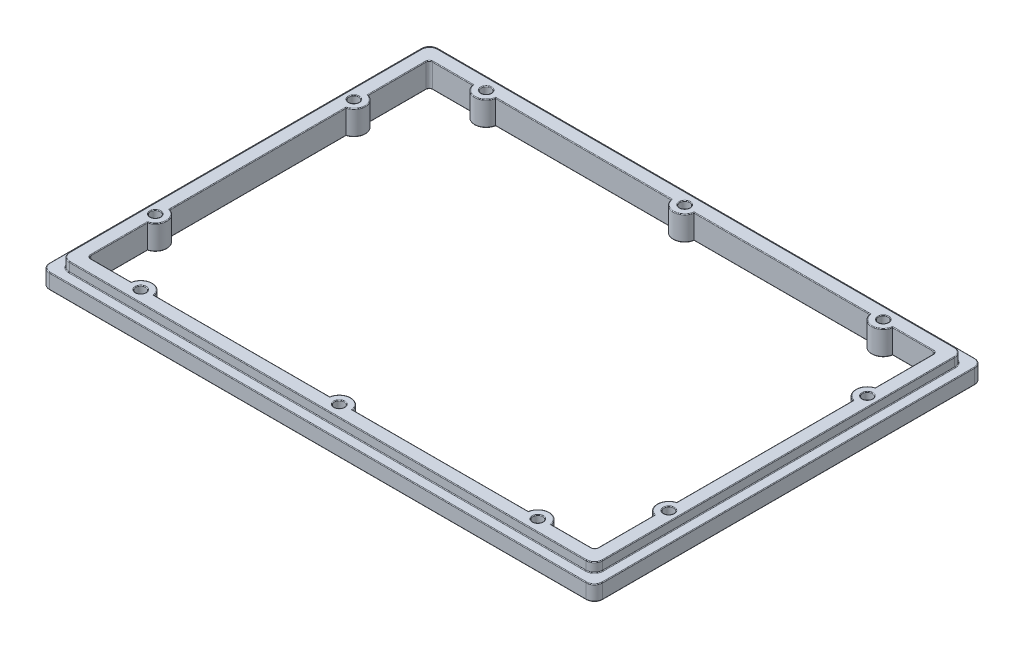
SolidWorks part; units mm, degrees
material "PP Copolymer"
ref_plane "Front Plane" through (0, 0, 0) normal (0, 0, 1) x (1, 0, 0)
ref_plane "Top Plane" through (0, 0, 0) normal (0, 1, 0) x (1, 0, 0)
ref_plane "Right Plane" through (0, 0, 0) normal (1, 0, 0) x (0, 0, -1)
sketch "Sketch1" plane through (0, 0, 0) normal (0, 1, 0) x (1, 0, 0)
  line L1 (-102.997, 74.549) -> (102.997, 74.549)
  line L2 (-106.172, 71.374) -> (-106.172, -71.374)
  line L3 (-102.997, -74.549) -> (102.997, -74.549)
  line L4 (106.172, 71.374) -> (106.172, -71.374)
  arc A0 (-102.997, 74.549) -> (-106.172, 71.374) centre (-102.997, 71.374) ccw
  arc A1 (-106.172, -71.374) -> (-102.997, -74.549) centre (-102.997, -71.374) ccw
  arc A2 (102.997, -74.549) -> (106.172, -71.374) centre (102.997, -71.374) ccw
  arc A3 (106.172, 71.374) -> (102.997, 74.549) centre (102.997, 71.374) ccw
  dimension "D5" = 3.175
  dimension "D1" = 212.344
  dimension "D2" = 106.172
  dimension "D3" = 149.098
  dimension "D4" = 74.549
extrude "Extrude1" add sketch "Sketch1" along normal blind 5.842
sketch "Sketch2" plane through (0, 5.842, 0) normal (0, 1, 0) x (1, 0, 0)
  line L0 (106.172, -71.374) -> (106.172, 71.374) construction
  line L1 (-99.187, 70.739) -> (99.187, 70.739)
  line L2 (-102.362, 67.564) -> (-102.362, -67.564)
  line L3 (-99.187, -70.739) -> (99.187, -70.739)
  line L4 (102.362, 67.564) -> (102.362, -67.564)
  line L5 (102.997, 74.549) -> (-102.997, 74.549) construction
  line L6 (-106.172, 71.374) -> (-106.172, -71.374) construction
  line L7 (-102.997, -74.549) -> (102.997, -74.549) construction
  arc A0 (-99.187, 70.739) -> (-102.362, 67.564) centre (-99.187, 67.564) ccw
  arc A1 (-102.362, -67.564) -> (-99.187, -70.739) centre (-99.187, -67.564) ccw
  arc A2 (99.187, -70.739) -> (102.362, -67.564) centre (99.187, -67.564) ccw
  arc A3 (102.362, 67.564) -> (99.187, 70.739) centre (99.187, 67.564) ccw
  dimension "D5" = 3.175
  dimension "D1" = 3.81
  dimension "D2" = 3.81
  dimension "D3" = 3.81
  dimension "D4" = 3.81
extrude "Extrude2" add sketch "Sketch2" along normal offset from surface (3.556 mm away) 9.398 up to face at (0, 0, 0)
sketch "Sketch3" plane through (0, 9.398, 0) normal (0, 1, 0) x (1, 0, 0)
  line L0 (80.5792, 65.532) -> (96.012, 65.532)
  line L1 (-96.012, 65.532) -> (-80.5792, 65.532)
  line L2 (-97.282, 64.262) -> (-97.282, 42.1057)
  line L3 (-96.012, -65.532) -> (-80.5792, -65.532)
  line L4 (97.282, 64.262) -> (97.282, 42.1057)
  line L5 (97.282, 33.5863) -> (97.282, -34.0943)
  line L6 (4.3792, 65.532) -> (71.8208, 65.532)
  line L7 (-71.8208, 65.532) -> (-4.3792, 65.532)
  line L8 (-97.282, 33.5863) -> (-97.282, -34.0943)
  line L9 (-97.282, -42.6137) -> (-97.282, -64.262)
  line L10 (-71.8208, -65.532) -> (-4.3792, -65.532)
  line L11 (4.3792, -65.532) -> (71.8208, -65.532)
  line L12 (97.282, -42.6137) -> (97.282, -64.262)
  line L13 (80.5792, -65.532) -> (96.012, -65.532)
  arc A0 (-96.012, 65.532) -> (-97.282, 64.262) centre (-96.012, 64.262) ccw
  arc A1 (96.012, 65.532) -> (97.282, 64.262) centre (96.012, 64.262) cw
  arc A2 (97.282, -64.262) -> (96.012, -65.532) centre (96.012, -64.262) cw
  arc A3 (-96.012, -65.532) -> (-97.282, -64.262) centre (-96.012, -64.262) cw
  arc A4 (-4.3792, 65.532) -> (4.3792, 65.532) centre (0, 66.294) ccw
  arc A5 (71.8208, 65.532) -> (80.5792, 65.532) centre (76.2, 66.294) ccw
  arc A6 (-80.5792, 65.532) -> (-71.8208, 65.532) centre (-76.2, 66.294) ccw
  arc A7 (-97.282, 33.5863) -> (-97.282, 42.1057) centre (-98.552, 37.846) ccw
  arc A8 (-97.282, -42.6137) -> (-97.282, -34.0943) centre (-98.552, -38.354) ccw
  arc A9 (4.3792, -65.532) -> (-4.3792, -65.532) centre (0, -66.294) ccw
  arc A10 (80.5792, -65.532) -> (71.8208, -65.532) centre (76.2, -66.294) ccw
  arc A11 (-71.8208, -65.532) -> (-80.5792, -65.532) centre (-76.2, -66.294) ccw
  arc A12 (97.282, 42.1057) -> (97.282, 33.5863) centre (98.552, 37.846) ccw
  arc A13 (97.282, -34.0943) -> (97.282, -42.6137) centre (98.552, -38.354) ccw
  dimension "D5" = 1.27
  dimension "D6" = 8.89
  dimension "D1" = 194.564
  dimension "D2" = 97.282
  dimension "D3" = 131.064
  dimension "D4" = 65.532
  dimension "D7" = 132.588
  dimension "D8" = 66.294
  dimension "D9" = 98.552
  dimension "D10" = 104.14
  dimension "D11" = 27.94
  dimension "D12" = 197.104
  dimension "D13" = 174.752
  dimension "D14" = 22.352
extrude "Extrude3" cut sketch "Sketch3" against normal through all
sketch "Sketch4" plane through (0, 9.398, 0) normal (0, 1, 0) x (1, 0, 0)
  circle A0 centre (-98.552, 37.846) radius 1.905
  circle A1 centre (-76.2, 66.294) radius 1.905
  circle A2 centre (0, 66.294) radius 1.905
  circle A3 centre (76.2, 66.294) radius 1.905
  circle A4 centre (98.552, 37.846) radius 1.905
  circle A5 centre (98.552, -38.354) radius 1.905
  circle A6 centre (76.2, -66.294) radius 1.905
  circle A7 centre (0, -66.294) radius 1.905
  circle A8 centre (-76.2, -66.294) radius 1.905
  circle A9 centre (-98.552, -38.354) radius 1.905
  arc A12 (71.8208, 65.532) -> (80.5792, 65.532) centre (76.2, 66.294) ccw construction
  arc A13 (-4.3792, 65.532) -> (4.3792, 65.532) centre (0, 66.294) ccw construction
  arc A14 (-80.5792, 65.532) -> (-71.8208, 65.532) centre (-76.2, 66.294) ccw construction
  arc A15 (-97.282, 33.5863) -> (-97.282, 42.1057) centre (-98.552, 37.846) ccw construction
  arc A16 (-97.282, -42.6137) -> (-97.282, -34.0943) centre (-98.552, -38.354) ccw construction
  arc A17 (-71.8208, -65.532) -> (-80.5792, -65.532) centre (-76.2, -66.294) ccw construction
  arc A18 (4.3792, -65.532) -> (-4.3792, -65.532) centre (0, -66.294) ccw construction
  arc A19 (80.5792, -65.532) -> (71.8208, -65.532) centre (76.2, -66.294) ccw construction
  arc A20 (97.282, -34.0943) -> (97.282, -42.6137) centre (98.552, -38.354) ccw construction
  arc A21 (97.282, 42.1057) -> (97.282, 33.5863) centre (98.552, 37.846) ccw construction
  dimension "D1" = 3.81
extrude "Extrude4" cut sketch "Sketch4" against normal through all
fillet "Fillet1" radius 0.254 108 edges at (-106.172, 0, 0) (-105.2421, 0, 73.6191) (0, 0, 74.549) (105.2421, 0, 73.6191) (106.172, 0, 0) (105.2421, 0, -73.6191) (-105.2421, 0, -73.6191) (-76.2, 0, -61.849) (-38.1, 0, -65.532) (0, 0, -61.849) (38.1, 0, -65.532) (76.2, 0, -61.849) (88.2956, 0, -65.532) (96.91, 0, -65.16) (97.282, 0, -53.1839) (94.107, 0, -37.846) (97.282, 0, 0.254) (94.107, 0, 38.354) (97.282, 0, 53.4379) (96.91, 0, 65.16) (88.2956, 0, 65.532) (76.2, 0, 61.849) (38.1, 0, 65.532) (0, 0, 61.849) (-38.1, 0, 65.532) (-76.2, 0, 61.849) (-88.2956, 0, 65.532) (-96.91, 0, 65.16) (-97.282, 0, 53.4379) (-94.107, 0, 38.354) (-97.282, 0, 0.254) (-94.107, 0, -37.846) (-97.282, 0, -53.1839) (-96.91, 0, -65.16) (-88.2956, 0, -65.532) (-98.552, 0, -35.941) (-76.2, 0, -64.389) (0, 0, -64.389) (76.2, 0, -64.389) (98.552, 0, -35.941) (98.552, 0, 40.259) (76.2, 0, 68.199) (0, 0, 68.199) (-76.2, 0, 68.199) (-98.552, 0, 40.259) (0, 0, -74.549) (-101.4321, 5.842, 69.8091) (0, 5.842, 70.739) (101.4321, 5.842, 69.8091) (102.362, 5.842, 0) (101.4321, 5.842, -69.8091) (0, 5.842, -70.739) (-101.4321, 5.842, -69.8091) (-102.362, 5.842, 0) (0, 5.842, -74.549) (105.2421, 5.842, -73.6191) (106.172, 5.842, 0) (105.2421, 5.842, 73.6191) (0, 5.842, 74.549) (-105.2421, 5.842, 73.6191) (-106.172, 5.842, 0) (-105.2421, 5.842, -73.6191) (101.4321, 9.398, -69.8091) (102.362, 9.398, 0) (101.4321, 9.398, 69.8091) (0, 9.398, 70.739) (-101.4321, 9.398, 69.8091) (-102.362, 9.398, 0) (-101.4321, 9.398, -69.8091) (0, 9.398, -70.739) (-97.282, 9.398, -53.1839) (-94.107, 9.398, -37.846) (-97.282, 9.398, 0.254) (-94.107, 9.398, 38.354) (-97.282, 9.398, 53.4379) (-96.91, 9.398, 65.16) (-88.2956, 9.398, 65.532) (-76.2, 9.398, 61.849) (-38.1, 9.398, 65.532) (0, 9.398, 61.849) (38.1, 9.398, 65.532) (76.2, 9.398, 61.849) (88.2956, 9.398, 65.532) (96.91, 9.398, 65.16) (97.282, 9.398, 53.4379) (94.107, 9.398, 38.354) (97.282, 9.398, 0.254) (94.107, 9.398, -37.846) (97.282, 9.398, -53.1839) (96.91, 9.398, -65.16) (88.2956, 9.398, -65.532) (76.2, 9.398, -61.849) (38.1, 9.398, -65.532) (0, 9.398, -61.849) (-38.1, 9.398, -65.532) (-76.2, 9.398, -61.849) (-88.2956, 9.398, -65.532) (-96.91, 9.398, -65.16) (-98.552, 9.398, -35.941) (-76.2, 9.398, -64.389) (0, 9.398, -64.389) (76.2, 9.398, -64.389) (98.552, 9.398, -35.941) (98.552, 9.398, 40.259) (76.2, 9.398, 68.199) (0, 9.398, 68.199) (-76.2, 9.398, 68.199) (-98.552, 9.398, 40.259)
